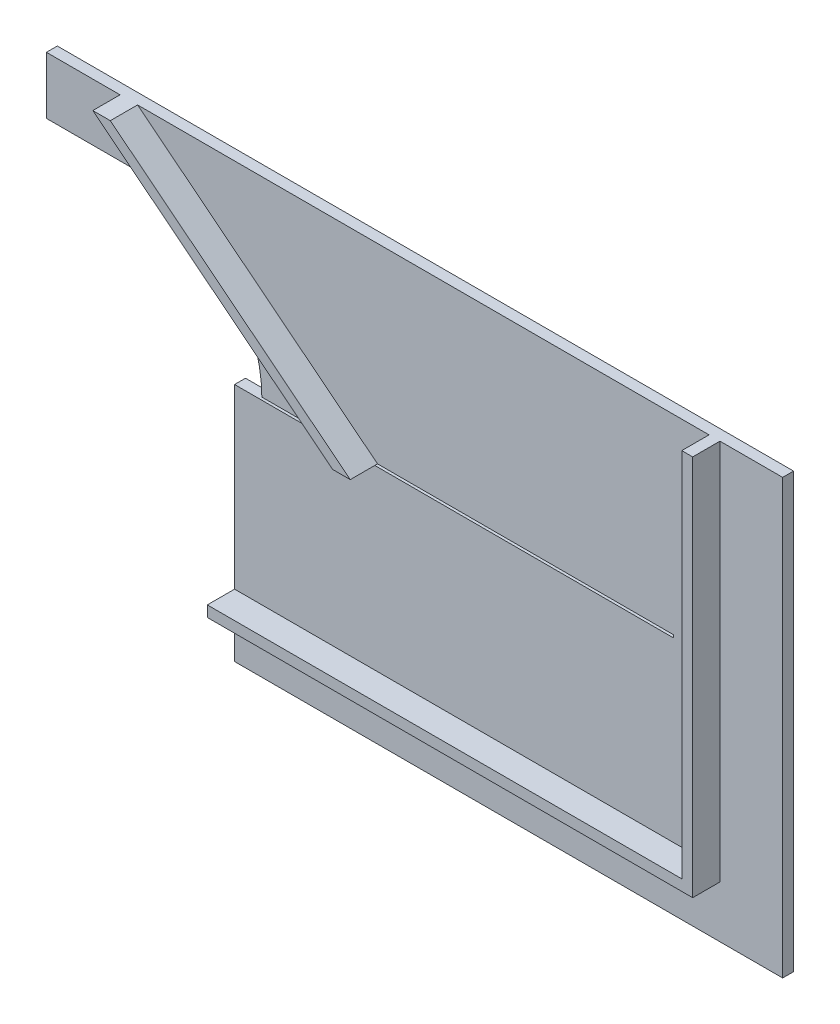
SolidWorks part; units mm, degrees
ref_plane "Front Plane" through (0, 0, 0) normal (0, 0, 1) x (1, 0, 0)
ref_plane "Top Plane" through (0, 0, 0) normal (0, 1, 0) x (1, 0, 0)
ref_plane "Right Plane" through (0, 0, 0) normal (1, 0, 0) x (0, 0, -1)
sketch "Sketch1" plane through (0, 0, 0) normal (0, 0, 1) x (1, 0, 0)
  line L0 (230, -159) -> (230, -70) construction
  line L1 (0, 0) -> (270, 0)
  line L2 (0, 0) -> (0, -21)
  line L3 (69, -70) -> (270, -70) construction
  line L4 (270, 0) -> (270, -70)
  line L5 (270, -159) -> (69, -159)
  line L6 (270, -159) -> (270, -70)
  line L7 (270, -70) -> (69, -70)
  line L8 (69, -159) -> (69, -70)
  line L10 (247, 0) -> (247, -140) construction
  line L11 (247, -140) -> (69, -140) construction
  line L12 (0, -21) -> (30, -21)
  line L13 (115, -70) -> (27, 0) construction
  line L14 (69, -71) -> (230, -71)
  line L15 (69, -71) -> (69, -70)
  line L16 (69, -70) -> (230, -70)
  line L17 (230, -71) -> (230, -70)
  arc A0 (30, -21) -> (79, -70) centre (30, -70) cw
  dimension "D10" = 49
  dimension "D1" = 270
  dimension "D2" = 70
  dimension "D3" = 89
  dimension "D4" = 40
  dimension "D5" = 161
  dimension "D6" = 23
  dimension "D7" = 19
  dimension "D8" = 21
  dimension "D9" = 30
  dimension "D11" = 36
  dimension "D12" = 27
  dimension "D13" = 1
extrude "Boss-Extrude1" add sketch "Sketch1" against normal blind 4 contours L12 A0 L7 L4 L1 L2 | L17 L14 L8 L5 L6 L7
sketch "Sketch2" plane through (0, 0, 0) normal (0, 0, 1) x (1, 0, 0)
  line L0 (230, -159) -> (230, -70) construction
  line L1 (0, 0) -> (270, 0) construction
  line L2 (0, 0) -> (0, -21) construction
  line L3 (69, -70) -> (270, -70) construction
  line L4 (270, 0) -> (270, -70) construction
  line L5 (270, -159) -> (69, -159) construction
  line L6 (270, -159) -> (270, -70) construction
  line L7 (270, -70) -> (69, -70) construction
  line L8 (69, -159) -> (69, -70) construction
  line L9 (247, 0) -> (247, -140)
  line L10 (247, -140) -> (69, -140)
  line L11 (0, -21) -> (30, -21) construction
  line L12 (115, -70) -> (27, 0)
  line L13 (69, -71) -> (230, -71) construction
  line L14 (69, -71) -> (69, -70) construction
  line L15 (69, -70) -> (230, -70) construction
  line L16 (230, -71) -> (230, -70) construction
  line L17 (243, 0) -> (243, -136)
  line L18 (243, -136) -> (69, -136)
  line L19 (117.4901, -66.8696) -> (33.4255, 0)
  line L20 (27, 0) -> (33.4255, 0)
  line L21 (117.4901, -66.8696) -> (121.4255, -70)
  line L22 (121.4255, -70) -> (115, -70)
  line L23 (69, -136) -> (69, -140)
  line L24 (243, 0) -> (247, 0)
  line L25 (117.4901, -66.8696) -> (29.4901, 3.1304) construction
  arc A0 (30, -21) -> (79, -70) centre (30, -70) cw construction
  dimension "D10" = 49
  dimension "D1" = 270
  dimension "D2" = 70
  dimension "D3" = 89
  dimension "D4" = 40
  dimension "D5" = 161
  dimension "D6" = 23
  dimension "D7" = 19
  dimension "D8" = 21
  dimension "D9" = 30
  dimension "D11" = 27
  dimension "D12" = 36
  dimension "D13" = 1
  dimension "D14" = 4
extrude "Boss-Extrude2" add sketch "Sketch2" along normal blind 10
